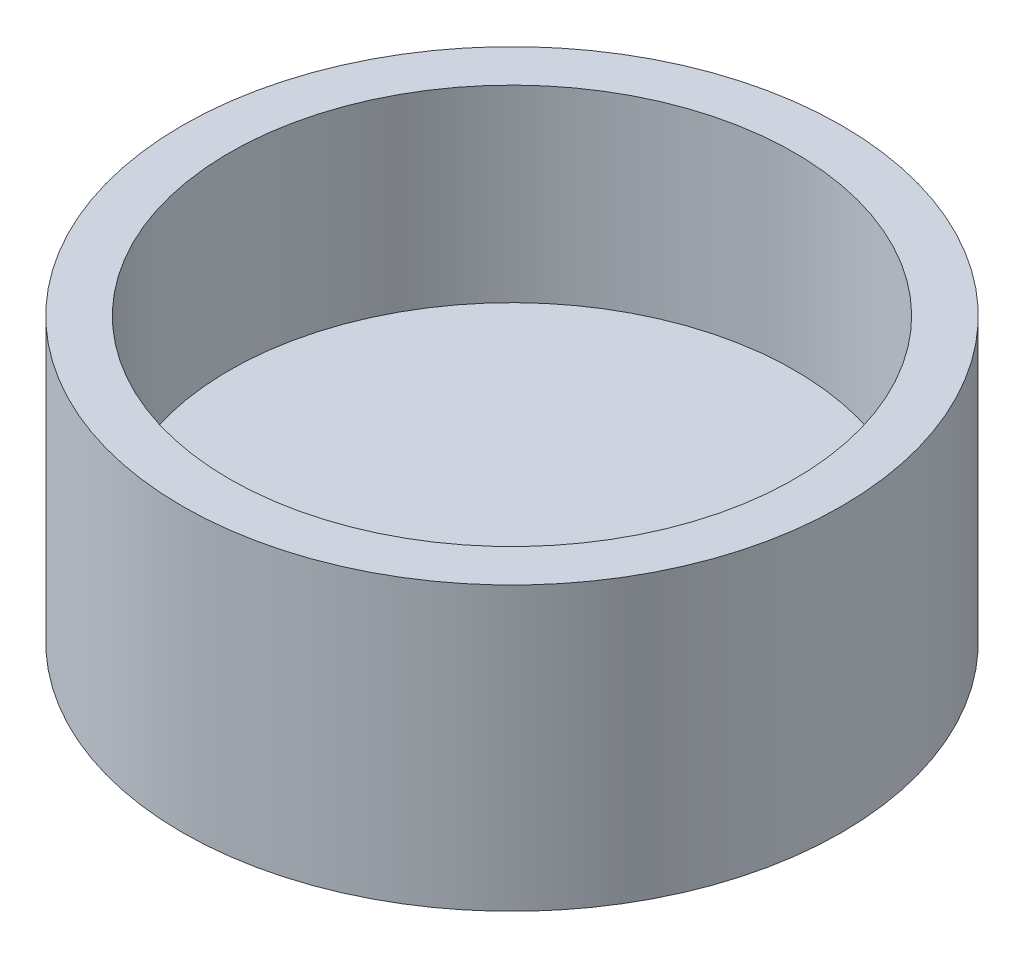
SolidWorks part; units mm, degrees
material "PE High Density"
ref_plane "Front Plane" through (0, 0, 0) normal (0, 0, 1) x (1, 0, 0)
ref_plane "Top Plane" through (0, 0, 0) normal (0, 1, 0) x (1, 0, 0)
ref_plane "Right Plane" through (0, 0, 0) normal (1, 0, 0) x (0, 0, -1)
sketch "Sketch1" plane through (0, 0, 0) normal (0, 1, 0) x (1, 0, 0)
  circle A0 centre (0, 0) radius 44.45
  dimension "D1" = 88.9
extrude "Boss-Extrude1" add sketch "Sketch1" along normal blind 38.1
sketch "Sketch2" plane through (0, 38.1, 0) normal (0, 1, 0) x (1, 0, 0)
  circle A0 centre (0, 0) radius 38.1
  dimension "D1" = 76.2
extrude "Cut-Extrude1" cut sketch "Sketch2" against normal blind 25.4
